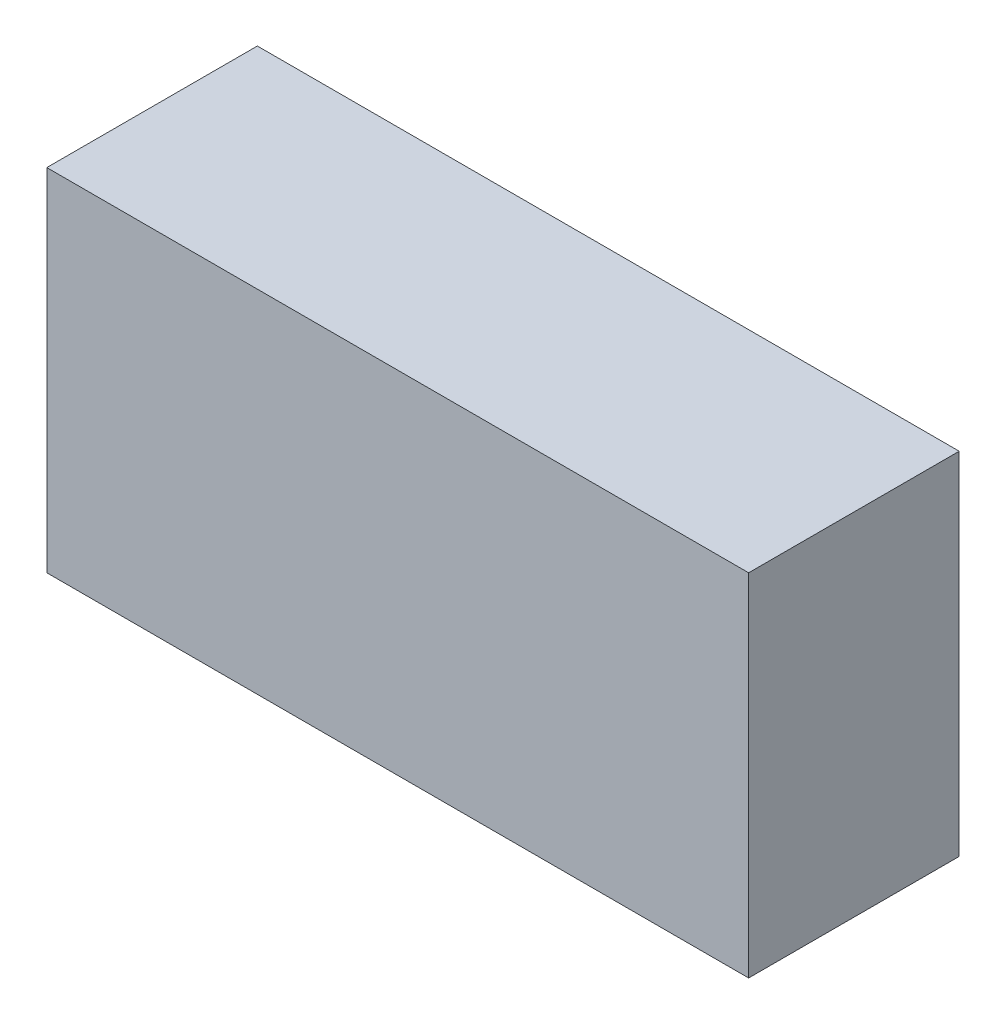
SolidWorks part; units mm, degrees
ref_plane "Front Plane" through (0, 0, 0) normal (0, 0, 1) x (1, 0, 0)
ref_plane "Top Plane" through (0, 0, 0) normal (0, 1, 0) x (1, 0, 0)
ref_plane "Right Plane" through (0, 0, 0) normal (1, 0, 0) x (0, 0, -1)
sketch "RectangleSketch" plane through (0, 0, 0) normal (0, 0, 1) x (1, 0, 0)
  line L1 (0, 0) -> (40, 0)
  line L2 (0, 0) -> (0, 20)
  line L3 (0, 20) -> (40, 20)
  line L4 (40, 0) -> (40, 20)
  dimension "width_mm" = 40
  dimension "height_mm" = 20
extrude "BlindBoss" add sketch "RectangleSketch" along normal blind 12 separate body
